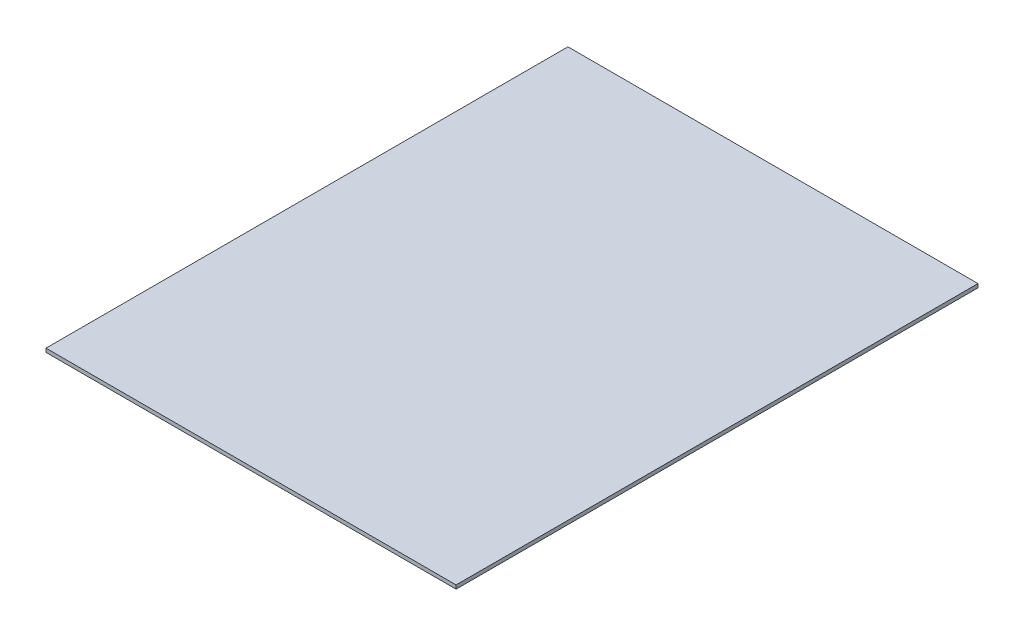
SolidWorks part; units mm, degrees
ref_plane "Front Plane" through (0, 0, 0) normal (0, 0, 1) x (1, 0, 0)
ref_plane "Top Plane" through (0, 0, 0) normal (0, 1, 0) x (1, 0, 0)
ref_plane "Right Plane" through (0, 0, 0) normal (1, 0, 0) x (0, 0, -1)
sketch "Sketch1" plane through (0, 0, 0) normal (0, 1, 0) x (1, 0, 0)
  line L1 (0, 0) -> (-550, 0)
  line L2 (0, 0) -> (0, -700)
  line L3 (0, -700) -> (-550, -700)
  line L4 (-550, 0) -> (-550, -700)
  dimension "D1" = 550
  dimension "D2" = 700
extrude "Boss-Extrude1" add sketch "Sketch1" along normal blind 5
